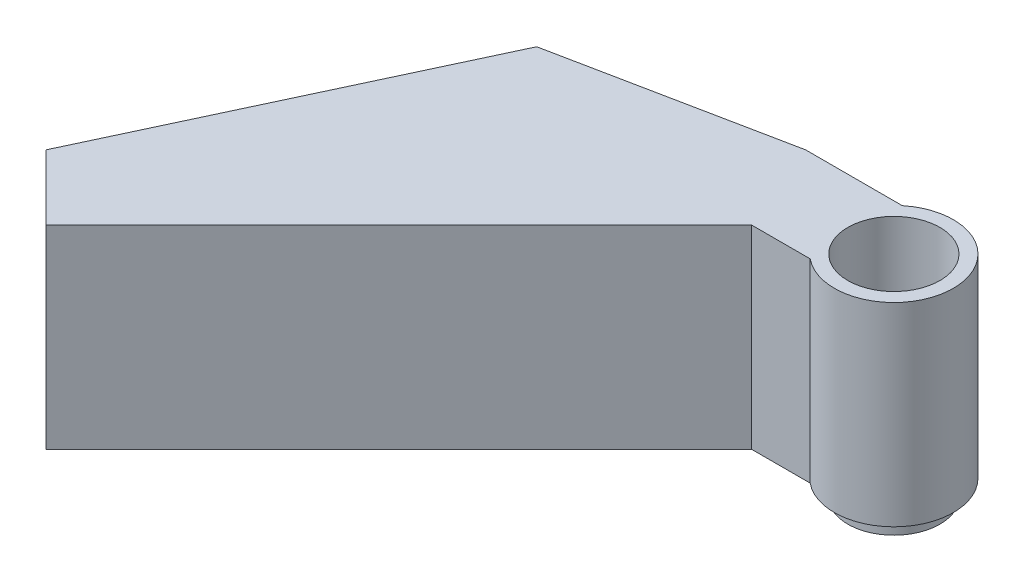
SolidWorks part; units mm, degrees
material "ABS"
ref_plane "Front Plane" through (0, 0, 0) normal (0, 0, 1) x (1, 0, 0)
ref_plane "Top Plane" through (0, 0, 0) normal (0, 1, 0) x (1, 0, 0)
ref_plane "Right Plane" through (0, 0, 0) normal (1, 0, 0) x (0, 0, -1)
sketch "Sketch1" plane through (0, 0, 0) normal (0, 1, 0) x (1, 0, 0)
  circle A0 centre (0, 0) radius 3.43
  circle A1 centre (0, 0) radius 1.235
  dimension "D1" = 6.86
  dimension "D2" = 2.47
extrude "main body" add sketch "Sketch1" along normal blind 4.715
sketch "Sketch2" plane through (0, 4.715, 0) normal (0, 1, 0) x (1, 0, 0)
  circle A0 centre (0, 0) radius 2.45
  dimension "D1" = 4.9
extrude "top screw hole" cut sketch "Sketch2" against normal blind 0.865
ref_plane "Plane1" through (0, 4.385, 0) normal (0, 1, 0) x (1, 0, 0)
sketch "Sketch3" plane through (0, 4.715, 0) normal (0, 1, 0) x (1, 0, 0)
  line L0 (0, 3.43) -> (-6.57, 3.43)
  line L1 (0, 0) -> (-6.57, 0) construction
  line L2 (0, -3.43) -> (-6.57, -3.43)
  line L3 (0, 0) -> (0, 8.1329) construction
  circle A0 centre (0, 0) radius 3.43 construction
  arc A1 (-6.57, 3.43) -> (-6.57, -3.43) centre (-6.57, 0) ccw
  circle A3 centre (0, 0) radius 3.43
  dimension "D2" = 10
extrude "make wings" add sketch "Sketch3" against normal offset from surface (14.465 mm away) 1.25 from offset 11
sketch "Sketch4" plane through (0, 0, 0) normal (0, -1, 0) x (1, 0, 0)
  circle A0 centre (0, 0) radius 2.5
  dimension "D1" = 5
extrude "spline hole" cut sketch "Sketch4" against normal blind 2.8
ref_plane "Plane2" through (-10, 0, 0) normal (-1, 0, 0) x (0, 0, 1)
sketch "Sketch5" plane through (-10, 0, 0) normal (-1, 0, 0) x (0, 0, 1)
  line L4 (-3.43, 1.25) -> (3.43, 1.25)
  line L5 (3.43, 1.25) -> (3.43, 15.715)
  line L6 (3.43, 15.715) -> (-3.43, 15.715)
  line L7 (-3.43, 15.715) -> (-3.43, 1.25)
  line L8 (-3.43, 1.25) -> (3.43, 1.25)
  line L9 (3.43, 1.25) -> (3.43, 15.715)
  line L10 (3.43, 15.715) -> (-3.43, 15.715)
  line L11 (-3.43, 15.715) -> (-3.43, 1.25)
  dimension "D1" = 0
extrude "Boss-Extrude1" add sketch "Sketch5" against normal blind 5
sketch "Sketch6" plane through (0, 15.715, 0) normal (0, 1, 0) x (1, 0, 0)
  line L0 (-10, 3.43) -> (-38.2843, -24.8543)
  line L1 (-38.2843, -24.8543) -> (-33.4335, -29.705)
  line L2 (-33.4335, -29.705) -> (-5.1492, -1.4208)
  line L3 (-10, 3.43) -> (-5.1492, -1.4208)
  line L6 (-10, -3.43) -> (-10, 3.43) construction
  line L7 (-10, 3.43) -> (-35.1051, 3.43) construction
  dimension "D1" = 45
  dimension "D2" = 40
extrude "Boss-Extrude2" add sketch "Sketch6" against normal up to surface (14.465 mm away) up to face at (-5.8575, 1.25, 0)
sketch "Sketch7" plane through (0, 15.715, 0) normal (0, 1, 0) x (1, 0, 0)
  line L0 (-38.2843, -24.8543) -> (-20.2946, 13.7246)
  line L1 (-20.2946, 13.7246) -> (-10, 3.43)
  line L2 (-10, 3.43) -> (-38.2843, -24.8543) construction
  line L3 (-10, 3.43) -> (-38.2843, -24.8543)
  dimension "D1" = 20
extrude "Boss-Extrude3" add sketch "Sketch7" against normal up to surface (14.465 mm away) up to face at (-15.3844, 1.25, 9.0932)
sketch "Sketch9" plane through (0, 15.715, 0) normal (0, 1, 0) x (1, 0, 0)
  line L0 (0, -4.43) -> (0, 4.43) construction
  line L1 (0, 3.43) -> (-2.8036, 3.43)
  line L2 (0, 3.43) -> (-10, 3.43) construction
  line L3 (0, -3.43) -> (-2.8036, -3.43)
  arc A0 (0, -3.43) -> (0, 3.43) centre (0, 0) ccw
  arc A1 (0, -3.43) -> (0, 3.43) centre (0, 0) ccw construction
  arc A2 (-2.8036, -3.43) -> (-2.8036, 3.43) centre (0, 0) ccw
  circle A4 centre (0, 0) radius 3.43 construction
  circle A5 centre (0, 0) radius 4.43 construction
  point P10 (3.2801, 1.0028)
  point P17 (4.43, 0)
  dimension "D1" = 1
extrude "Boss-Extrude4" add sketch "Sketch9" against normal up to surface (14.465 mm away) up to face at (-16.0858, 1.25, 5.8335)
sketch "Sketch10" plane through (0, 15.715, 0) normal (0, 1, 0) x (1, 0, 0)
  line L0 (-10, 3.43) -> (-26.6638, 0.0659)
  line L1 (-10, 3.43) -> (-20.2946, 13.7246) construction
  line L2 (-20.2946, 13.7246) -> (-38.2843, -24.8543) construction
  line L3 (-20.2946, 13.7246) -> (-26.6638, 0.0659)
  line L4 (-20.2946, 13.7246) -> (-10, 3.43)
  line L5 (-2.8036, 3.43) -> (-10, 3.43) construction
  dimension "D1" = 17
extrude "Cut-Extrude1" cut sketch "Sketch10" against normal through all
